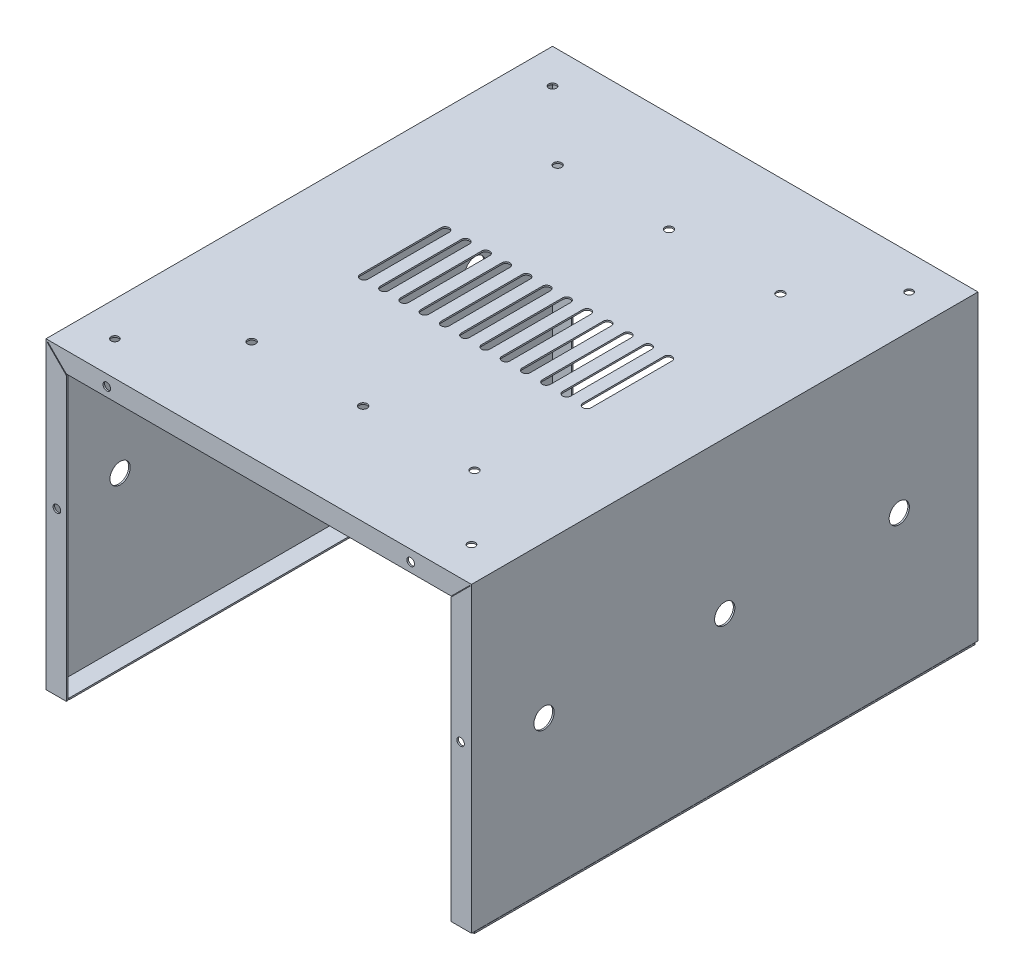
SolidWorks part; units mm, degrees
ref_plane "Alzado" through (0, 0, 0) normal (0, 0, 1) x (1, 0, 0)
ref_plane "Planta" through (0, 0, 0) normal (0, 1, 0) x (1, 0, 0)
ref_plane "Vista lateral" through (0, 0, 0) normal (1, 0, 0) x (0, 0, -1)
sketch "Croquis1" plane through (0, 0, 0) normal (0, 0, 1) x (1, 0, 0)
  line L0 (-105, 0) -> (-105, 150)
  line L1 (-105, 150) -> (105, 150)
  line L2 (105, 150) -> (105, 0.8638)
  line L3 (-105, 0) -> (-104.25, 0)
  line L4 (-104.25, 0) -> (-104.25, 149.25)
  line L5 (-104.25, 149.25) -> (104.25, 149.25)
  line L6 (104.25, 149.25) -> (104.25, 0.8638)
  line L7 (104.25, 0.8638) -> (105, 0.8638)
  point P2 (0, 150)
  dimension "D1" = 150
  dimension "D2" = 210
  dimension "D3" = 0.75
  dimension "D4" = 0.75
  dimension "D5" = 0.75
extrude "Saliente-Extruir1" add sketch "Croquis1" against normal blind 250
sketch "Croquis2" plane through (-105, 0, 0) normal (-1, 0, 0) x (0, 0, 1)
  circle A0 centre (-238.968, 123.1215) radius 5
  dimension "D1" = 10
extrude "Cortar-Extruir1" cut sketch "Croquis2" against normal blind 41
sketch "Croquis3" plane through (0, 0, 0) normal (0, 0, 1) x (1, 0, 0)
  line L0 (-105, 150) -> (-95, 140)
  line L1 (-95, 140) -> (95, 140)
  line L2 (95, 140) -> (105, 150)
  line L3 (-105, 150) -> (-105, 0) construction
  line L5 (105, 0.8638) -> (105, 150) construction
  line L6 (-105, 149.3851) -> (-95, 139.3851)
  line L7 (-95, 139.3851) -> (-95, 0)
  line L8 (-95, 0) -> (-105, 0)
  line L9 (-105, 0) -> (-105, 149.3851)
  line L10 (-105, 150) -> (105, 150)
  line L11 (105, 149.6157) -> (95, 139.6157)
  line L12 (95, 139.6157) -> (95, 0.8638)
  line L13 (95, 0.8638) -> (105, 0.8638)
  line L14 (105, 0.8638) -> (105, 149.6157)
  dimension "D1" = 10
  dimension "D2" = 10
extrude "Saliente-Extruir2" add sketch "Croquis3" against normal blind 0.75
sketch "Croquis4" plane through (0, 0, -250) normal (0, 0, -1) x (-1, 0, 0)
  line L0 (-105, 150) -> (-95, 140)
  line L1 (-95, 140) -> (95, 140)
  line L2 (95, 140) -> (105, 150)
  line L3 (105, 150) -> (-105, 150)
  line L4 (105, 149.2707) -> (95, 139.3851)
  line L5 (105, 150) -> (105, 0) construction
  line L6 (95, 139.3851) -> (95, 0)
  line L7 (95, 0) -> (105, 0)
  line L8 (105, 0) -> (105, 149.2707)
  line L9 (-95, 139.6157) -> (-105, 149.6157)
  line L10 (-105, 0.8638) -> (-105, 150) construction
  line L11 (-105, 149.6157) -> (-105, 0.8638)
  line L12 (-105, 0.8638) -> (-95, 0.8638)
  line L13 (-95, 0.8638) -> (-95, 139.6157)
extrude "Saliente-Extruir3" add sketch "Croquis4" against normal blind 0.75
sketch "Croquis6" plane through (0, 0, 0) normal (0, -1, 0) x (1, 0, 0)
  line L0 (-105, -1.3812) -> (-94.964, -1.3812)
  line L1 (-105, -250) -> (-105, 0) construction
  line L2 (-94.964, -1.3812) -> (-94.964, -248.559)
  line L3 (-94.964, -248.559) -> (-105, -248.559)
  line L4 (-105, -248.559) -> (-105, -1.3812)
  line L5 (95.111, -1.3812) -> (105, -1.3812)
  line L6 (105, -250) -> (105, 0) construction
  line L7 (105, -1.3812) -> (105, -248.559)
  line L8 (105, -248.559) -> (95.111, -248.559)
  line L9 (95.111, -248.559) -> (95.111, -1.3812)
extrude "Saliente-Extruir4" add sketch "Croquis6" against normal blind 0.75
sketch "Croquis7" plane through (0, 150, 0) normal (0, 1, 0) x (1, 0, 0)
  line L0 (105, 250) -> (-105, 250) construction
  line L1 (-105, 250) -> (-105, 0) construction
  line L2 (105, 250) -> (105, 0) construction
  line L3 (105, 0) -> (-105, 0) construction
  circle A0 centre (-88, 233) radius 1.875
  circle A1 centre (88, 233) radius 1.875
  circle A2 centre (88, 17) radius 1.875
  circle A3 centre (-88, 17) radius 1.875
  dimension "D1" = 3.75
  dimension "D2" = 17
  dimension "D3" = 17
  dimension "D4" = 17
  dimension "D5" = 17
extrude "Cortar-Extruir2" cut sketch "Croquis7" against normal blind 25.75
sketch "Croquis8" plane through (0, 150, 0) normal (0, 1, 0) x (1, 0, 0)
  line L0 (-105, 125) -> (105, 125) construction
  line L1 (-105, 250) -> (-105, 0) construction
  line L2 (105, 250) -> (105, 0) construction
  line L3 (-55, 145) -> (-55, 105)
  line L5 (-51, 105) -> (-51, 145)
  line L7 (-41, 105) -> (-41, 145)
  line L8 (-45, 145) -> (-45, 105)
  line L9 (-31, 105) -> (-31, 145)
  line L10 (-35, 145) -> (-35, 105)
  line L11 (-21, 105) -> (-21, 145)
  line L12 (-25, 145) -> (-25, 105)
  line L13 (-11, 105) -> (-11, 145)
  line L14 (-15, 145) -> (-15, 105)
  line L15 (-1, 105) -> (-1, 145)
  line L16 (-5, 145) -> (-5, 105)
  line L17 (9, 105) -> (9, 145)
  line L18 (5, 145) -> (5, 105)
  line L19 (19, 105) -> (19, 145)
  line L20 (15, 145) -> (15, 105)
  line L21 (29, 105) -> (29, 145)
  line L22 (25, 145) -> (25, 105)
  line L23 (39, 105) -> (39, 145)
  line L24 (35, 145) -> (35, 105)
  line L25 (49, 105) -> (49, 145)
  line L26 (45, 145) -> (45, 105)
  line L29 (59, 105) -> (59, 145)
  line L30 (55, 145) -> (55, 105)
  arc A0 (-55, 145) -> (-51, 145) centre (-53, 145) cw
  arc A1 (-55, 105) -> (-51, 105) centre (-53, 105) ccw
  arc A2 (-45, 105) -> (-41, 105) centre (-43, 105) ccw
  arc A3 (-45, 145) -> (-41, 145) centre (-43, 145) cw
  arc A4 (-35, 105) -> (-31, 105) centre (-33, 105) ccw
  arc A5 (-35, 145) -> (-31, 145) centre (-33, 145) cw
  arc A6 (-25, 105) -> (-21, 105) centre (-23, 105) ccw
  arc A7 (-25, 145) -> (-21, 145) centre (-23, 145) cw
  arc A8 (-15, 105) -> (-11, 105) centre (-13, 105) ccw
  arc A9 (-15, 145) -> (-11, 145) centre (-13, 145) cw
  arc A10 (-5, 105) -> (-1, 105) centre (-3, 105) ccw
  arc A11 (-5, 145) -> (-1, 145) centre (-3, 145) cw
  arc A12 (5, 105) -> (9, 105) centre (7, 105) ccw
  arc A13 (5, 145) -> (9, 145) centre (7, 145) cw
  arc A14 (15, 105) -> (19, 105) centre (17, 105) ccw
  arc A15 (15, 145) -> (19, 145) centre (17, 145) cw
  arc A16 (25, 105) -> (29, 105) centre (27, 105) ccw
  arc A17 (25, 145) -> (29, 145) centre (27, 145) cw
  arc A18 (35, 105) -> (39, 105) centre (37, 105) ccw
  arc A19 (35, 145) -> (39, 145) centre (37, 145) cw
  arc A20 (45, 105) -> (49, 105) centre (47, 105) ccw
  arc A21 (45, 145) -> (49, 145) centre (47, 145) cw
  arc A24 (55, 105) -> (59, 105) centre (57, 105) ccw
  arc A25 (55, 145) -> (59, 145) centre (57, 145) cw
  point P9 (-55, 125)
  dimension "D1" = 40
  dimension "D2" = 4
  dimension "D3" = 50
  dimension "D4" = 12
extrude "Cortar-Extruir3" cut sketch "Croquis8" against normal blind 25.75
sketch "Croquis9" plane through (0, 0, 0) normal (0, 0, 1) x (1, 0, 0)
  line L0 (-105, 0) -> (-95, 0) construction
  line L1 (0, 0) -> (0, 154.3261) construction
  line L2 (-105, 150) -> (-105, 0) construction
  circle A0 centre (-99.6255, 80) radius 1.875
  circle A1 centre (-75, 144.5718) radius 1.875
  circle A2 centre (99.6255, 80) radius 1.875
  circle A3 centre (75, 144.5718) radius 1.875
  dimension "D2" = 3.75
  dimension "D3" = 3.75
  dimension "D1" = 80
  dimension "D4" = 30
extrude "Cortar-Extruir4" cut sketch "Croquis9" against normal blind 269.75
sketch "Croquis10" plane through (105, 0, 0) normal (1, 0, 0) x (0, 0, -1)
  line L0 (125, 150) -> (125, 75) construction
  line L2 (250, 150) -> (0, 150) construction
  circle A0 centre (125, 75) radius 5
  circle A1 centre (211.1455, 75) radius 5
  circle A2 centre (35.8218, 75) radius 5
  circle A3 centre (125, 75) radius 15 construction
  circle A4 centre (125, 75) radius 10 construction
  dimension "D2" = 10
  dimension "D4" = 30
  dimension "D5" = 20
  dimension "D1" = 75
extrude "Cortar-Extruir5" cut sketch "Croquis10" against normal blind 269.75
sketch "Croquis11" plane through (0, 149.25, 0) normal (0, -1, 0) x (1, 0, 0)
  line L0 (-55, -105) -> (-55, -145) construction
  line L1 (-75, -47.5) -> (-31, -47.5) construction
  line L2 (-75, -47.5) -> (-75, -202.5) construction
  line L3 (-75, -202.5) -> (-31, -202.5) construction
  line L4 (-31, -47.5) -> (-31, -202.5) construction
  line L5 (-20, -47.5) -> (-20, -202.5) construction
  line L6 (-20, -47.5) -> (24, -47.5) construction
  line L7 (24, -47.5) -> (24, -202.5) construction
  line L8 (-20, -202.5) -> (24, -202.5) construction
  line L9 (35, -47.5) -> (35, -202.5) construction
  line L10 (35, -47.5) -> (79, -47.5) construction
  line L11 (79, -47.5) -> (79, -202.5) construction
  line L12 (35, -202.5) -> (79, -202.5) construction
  circle A0 centre (-53, -49.5) radius 2
  circle A1 centre (2, -49.5) radius 2
  circle A2 centre (57, -49.5) radius 2
  circle A3 centre (2, -200.5) radius 2
  circle A4 centre (57, -200.5) radius 2
  circle A7 centre (-53, -200.5) radius 2
  point P6 (-55, -125)
  point P7 (-75, -125)
  point P19 (-53, -47.5)
  dimension "D4" = 4
  dimension "D1" = 44
  dimension "D2" = 155
  dimension "D3" = 3
  dimension "D5" = 3
  dimension "D6" = 2
extrude "Cortar-Extruir6" cut sketch "Croquis11" against normal blind 10
